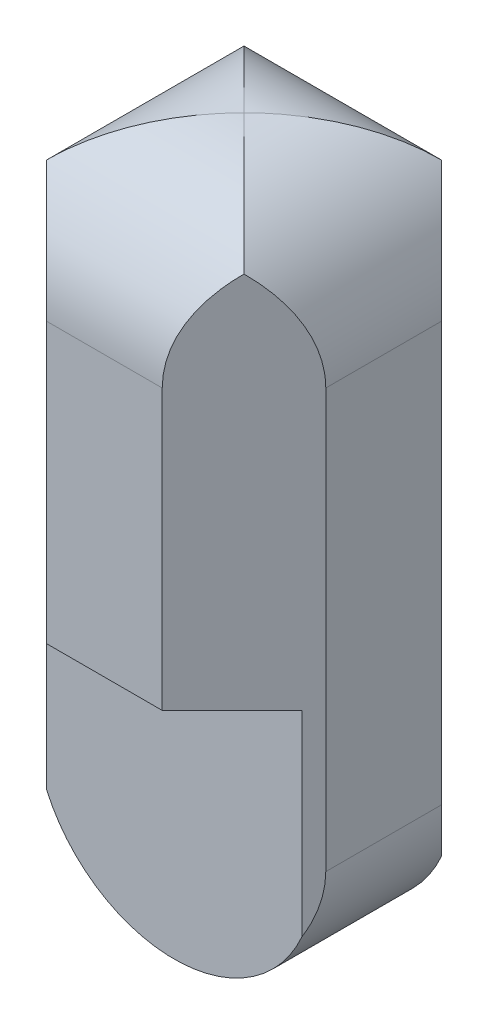
SolidWorks part; units mm, degrees
ref_plane "Front" through (0, 0, 0) normal (0, 0, 1) x (1, 0, 0)
ref_plane "Top" through (0, 0, 0) normal (0, 1, 0) x (1, 0, 0)
ref_plane "Right" through (0, 0, 0) normal (1, 0, 0) x (0, 0, -1)
sketch "草图1" plane through (0, 0, 0) normal (0, 1, 0) x (1, 0, 0)
  line L0 (-12.6518, 0) -> (13.462, 0) construction
  line L1 (0, 11.6722) -> (0, -14.1269) construction
  line L3 (10, 4.1421) -> (4.1421, 10)
  line L4 (4.1421, 10) -> (-4.1421, 10)
  line L5 (-4.1421, 10) -> (-10, 4.1421)
  line L6 (-10, 4.1421) -> (-10, -4.1421)
  line L7 (-10, -4.1421) -> (-4.1421, -10)
  line L8 (-4.1421, -10) -> (4.1421, -10)
  line L9 (4.1421, -10) -> (10, -4.1421)
  line L10 (10, -4.1421) -> (10, 4.1421)
  circle A0 centre (0, 0) radius 10 construction
extrude "凸台-拉伸1" add sketch "草图1" along normal blind 50
sketch "草图2" plane through (0, 0, 10) normal (0, 0, 1) x (1, 0, 0)
  line L0 (0, 0) -> (0, 24) construction
  line L7 (-10, 10) -> (-10, -2.3893)
  line L8 (-10, -2.3893) -> (10, -2.3893)
  line L9 (10, 10) -> (10, -2.3893)
  arc A1 (-10, 10) -> (10, 10) centre (0, 10) ccw
extrude "切除-拉伸1" cut sketch "草图2" against normal blind 66
sketch "草图4" plane through (0, 0, 10) normal (0, 0, 1) x (1, 0, 0)
  line L0 (10, 50) -> (10, 10) construction
  line L2 (-10, 10) -> (-10, 20)
  line L3 (-10, 20) -> (10, 20)
  line L4 (10, 10) -> (10, 20)
  arc A0 (-10, 10) -> (10, 10) centre (0, 10) ccw
extrude "切除-拉伸2" cut sketch "草图4" against normal blind 5
sketch "草图5" plane through (0, 0, -10) normal (0, 0, -1) x (-1, 0, 0)
  line L0 (10, 50) -> (10, 10) construction
  line L2 (-10, 10) -> (-10, 20)
  line L3 (-10, 20) -> (10, 20)
  line L4 (10, 10) -> (10, 20)
  arc A0 (-10, 10) -> (10, 10) centre (0, 10) ccw
extrude "切除-拉伸3" cut sketch "草图5" against normal blind 5
sketch "草图7" plane through (0, 0, 10) normal (0, 0, 1) x (1, 0, 0)
  line L0 (0, 50) -> (0, 0) construction
  line L1 (-4.1421, 50) -> (4.1421, 50) construction
  line L4 (-10, 40) -> (-10, 52.61)
  line L5 (-10, 52.61) -> (10, 52.61)
  line L6 (10, 40) -> (10, 52.61)
  arc A0 (10, 40) -> (-10, 40) centre (0, 40) ccw
extrude "切除-拉伸5" cut sketch "草图7" against normal blind 30
sketch "草图8" plane through (10, 0, 0) normal (1, 0, 0) x (0, 0, -1)
  line L0 (0, 50) -> (0, 0) construction
  line L1 (10, 50) -> (-10, 50) construction
  line L4 (-10, 40) -> (-10, 54.5623)
  line L5 (-10, 54.5623) -> (10, 54.5623)
  line L6 (10, 40) -> (10, 54.5623)
  arc A0 (10, 40) -> (-10, 40) centre (0, 40) ccw
  dimension "D1" = 10
extrude "切除-拉伸6" cut sketch "草图8" against normal blind 30
